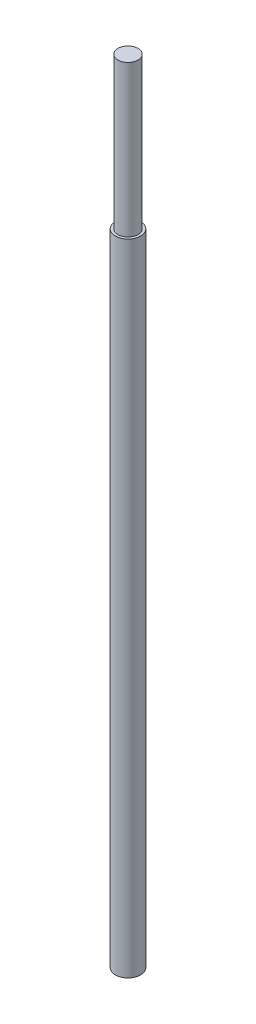
SolidWorks part; units mm, degrees
material "Chrome Stainless Steel"
ref_plane "Front Plane" through (0, 0, 0) normal (0, 0, 1) x (1, 0, 0)
ref_plane "Top Plane" through (0, 0, 0) normal (0, 1, 0) x (1, 0, 0)
ref_plane "Right Plane" through (0, 0, 0) normal (1, 0, 0) x (0, 0, -1)
sketch "Sketch1" plane through (0, 0, 0) normal (0, 1, 0) x (1, 0, 0)
  circle A0 centre (0, 0) radius 5
  dimension "D1" = 10
extrude "Boss-Extrude1" add sketch "Sketch1" along normal blind 254
sketch "Sketch2" plane through (0, 254, 0) normal (0, 1, 0) x (1, 0, 0)
  circle A0 centre (0, 0) radius 4
  circle A1 centre (0, 0) radius 5 construction
  dimension "D1" = 8
  dimension "D2" = 0
extrude "Boss-Extrude2" add sketch "Sketch2" along normal blind 60
